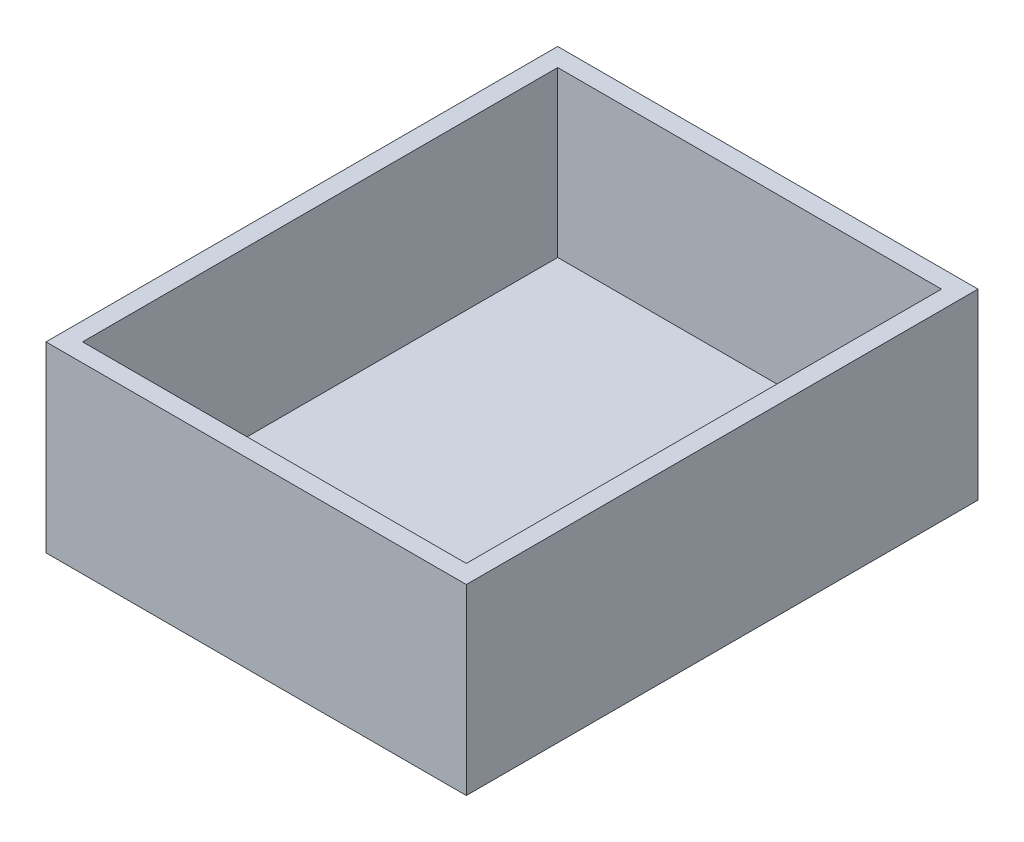
SolidWorks part; units mm, degrees
material "Balsa"
ref_plane "Front Plane" through (0, 0, 0) normal (0, 0, 1) x (1, 0, 0)
ref_plane "Top Plane" through (0, 0, 0) normal (0, 1, 0) x (1, 0, 0)
ref_plane "Right Plane" through (0, 0, 0) normal (1, 0, 0) x (0, 0, -1)
sketch "Sketch1" plane through (0, 0, 0) normal (0, 1, 0) x (1, 0, 0)
  line L1 (-57.5, 70) -> (57.5, 70)
  line L2 (-57.5, 70) -> (-57.5, -70)
  line L3 (-57.5, -70) -> (57.5, -70)
  line L4 (57.5, 70) -> (57.5, -70)
  line L5 (-57.5, 70) -> (57.5, -70) construction
  line L6 (-57.5, -70) -> (57.5, 70) construction
  point P0 (0, 0)
  dimension "D1" = 115
  dimension "D2" = 140
extrude "Boss-Extrude1" add sketch "Sketch1" along normal blind 50
sketch "Sketch2" plane through (0, 50, 0) normal (0, 1, 0) x (1, 0, 0)
  line L0 (-0.2275, 70) -> (0, 65) construction
  line L1 (-52.4948, 65) -> (52.4948, 65)
  line L2 (-52.4948, 65) -> (-52.4948, -65)
  line L3 (-52.4948, -65) -> (52.4948, -65)
  line L4 (52.4948, 65) -> (52.4948, -65)
  line L5 (-52.4948, 65) -> (52.4948, -65) construction
  line L6 (-52.4948, -65) -> (52.4948, 65) construction
  line L7 (57.5, 70) -> (-57.5, 70) construction
  line L8 (-57.5, 0) -> (-52.4948, 0) construction
  line L9 (-57.5, 70) -> (-57.5, -70) construction
  point P0 (0, 0)
  dimension "D1" = 5
extrude "Cut-Extrude1" cut sketch "Sketch2" against normal offset from surface (45 mm away) 5 up to face at (0, 0, 0)
ref_plane "Plane2" through (0, 0, 0) normal (0, -1, 0) x (-1, 0, 0)
sketch "Sketch3" plane through (0, 0, 0) normal (0, -1, 0) x (-1, 0, 0)
  line L0 (0, 70) -> (0, -70)
  line L1 (-57.5, 70) -> (57.5, 70) construction
  line L2 (57.5, -70) -> (-57.5, -70) construction
  point P3 (0, 0)
